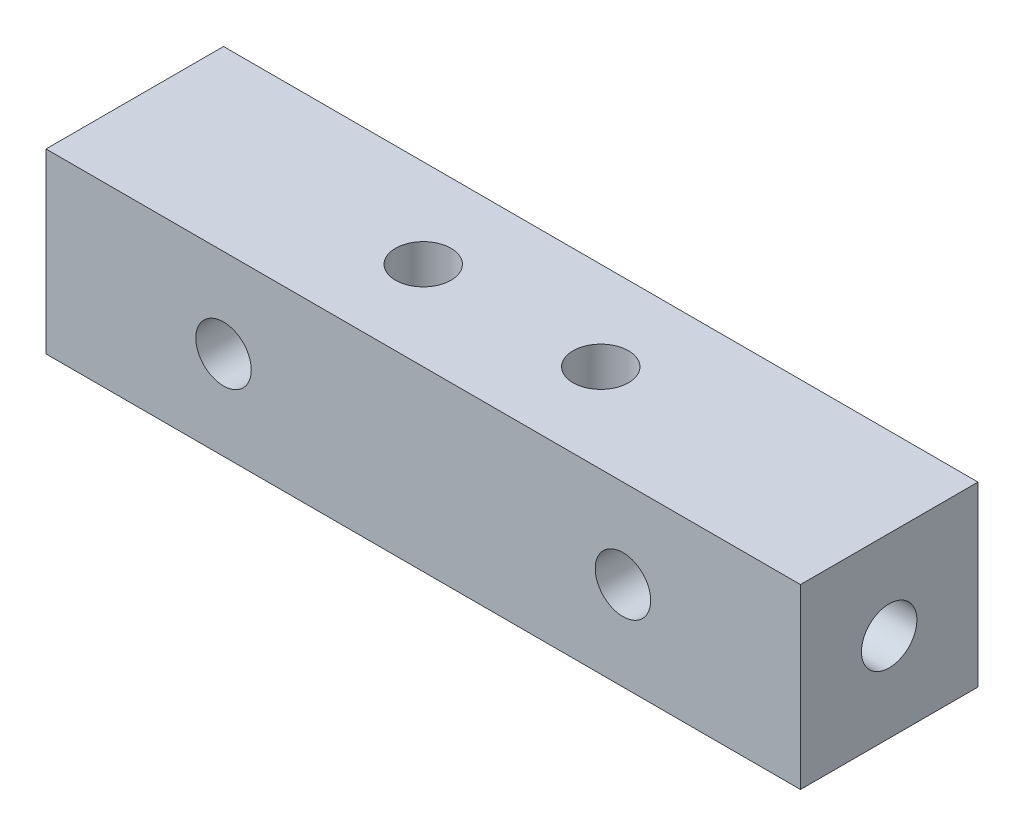
SolidWorks part; units mm, degrees
material "6061 合金"
ref_plane "前视基准面" through (0, 0, 0) normal (0, 0, 1) x (1, 0, 0)
ref_plane "上视基准面" through (0, 0, 0) normal (0, 1, 0) x (1, 0, 0)
ref_plane "右视基准面" through (0, 0, 0) normal (1, 0, 0) x (0, 0, -1)
sketch "草图1" plane through (0, 0, 0) normal (0, 0, 1) x (1, 0, 0)
  line L1 (17, -4) -> (-17, -4)
  line L2 (17, -4) -> (17, 4)
  line L3 (17, 4) -> (-17, 4)
  line L4 (-17, -4) -> (-17, 4)
  line L5 (17, -4) -> (-17, 4) construction
  line L6 (17, 4) -> (-17, -4) construction
  point P0 (0, 0)
  dimension "D1" = 34
  dimension "D2" = 8
extrude "凸台-拉伸1" add sketch "草图1" along normal blind 8
sketch "草图4" plane through (17, 0, 0) normal (1, 0, 0) x (0, 0, -1)
  line L0 (-8, 4) -> (0, -4) construction
  line L1 (0, 4) -> (-8, -4) construction
  point P8 (-4.0037, 0)
sketch "草图7" plane through (17, 0, 0) normal (1, 0, 0) x (0, 0, -1)
  line L0 (-8, 4) -> (0, -4) construction
  line L1 (0, 4) -> (-8, -4) construction
hole_wizard "M3 螺纹孔的螺纹孔钻头2" positions "3D草图6" profile "草图10" hole size "M3" standard "DIN" end condition through all
sketch3d "3D草图6"
  point P0 (17, 0, 4.0037)
sketch "草图10" plane through (17, 0, 4.0037) normal (0, 1, 0) x (0, 0, -1)
  line L0 (0, 0) -> (0, 34)
  line L1 (0, 34) -> (1.25, 34)
  line L2 (1.25, 34) -> (1.25, 0)
  line L5 (1.25, 0) -> (0, 0)
  line L11 (0, -6.35) -> (0, 107.95) construction
  dimension "通孔孔直径" = 2.5
  dimension "通孔孔深度" = 34
sketch "草图11" plane through (0, 0, 8) normal (0, 0, 1) x (1, 0, 0)
  line L0 (-17, 4) -> (-17, -4) construction
  point P0 (-9, 0)
  dimension "D1" = 8
hole_wizard "M3 螺纹孔的螺纹孔钻头3" positions "3D草图7" profile "草图12" hole size "M3" standard "DIN" end condition through all
sketch3d "3D草图7"
  point P0 (-9, 0, 8)
sketch "草图12" plane through (-9, 0, 8) normal (1, 0, 0) x (0, -1, 0)
  line L0 (0, 0) -> (0, 8)
  line L1 (0, 8) -> (1.25, 8)
  line L2 (1.25, 8) -> (1.25, 0)
  line L5 (1.25, 0) -> (0, 0)
  line L11 (0, -6.35) -> (0, 107.95) construction
  dimension "通孔孔直径" = 2.5
  dimension "通孔孔深度" = 8
sketch "草图13" plane through (0, 0, 8) normal (0, 0, 1) x (1, 0, 0)
  line L0 (17, -4) -> (17, 4) construction
  point P0 (9, 0)
  dimension "D1" = 8
hole_wizard "M3 螺纹孔的螺纹孔钻头4" positions "3D草图8" profile "草图14" hole size "M3" standard "DIN" end condition through all
sketch3d "3D草图8"
  point P0 (9, 0, 8)
sketch "草图14" plane through (9, 0, 8) normal (1, 0, 0) x (0, -1, 0)
  line L0 (0, 0) -> (0, 8)
  line L1 (0, 8) -> (1.25, 8)
  line L2 (1.25, 8) -> (1.25, 0)
  line L5 (1.25, 0) -> (0, 0)
  line L11 (0, -6.35) -> (0, 107.95) construction
  dimension "通孔孔直径" = 2.5
  dimension "通孔孔深度" = 8
sketch "草图15" plane through (0, 4, 0) normal (0, 1, 0) x (1, 0, 0)
  line L0 (17, 0) -> (-17, 0) construction
  line L1 (-17, -8) -> (-17, 0) construction
  point P0 (-4, -4)
  dimension "D1" = 4
  dimension "D2" = 13
hole_wizard "M3 螺纹孔的螺纹孔钻头5" positions "3D草图9" profile "草图16" hole size "M3" standard "DIN" end condition through all
sketch3d "3D草图9"
  point P0 (-4, 4, 4)
sketch "草图16" plane through (-4, 4, 4) normal (1, 0, 0) x (0, 0, 1)
  line L0 (0, 0) -> (0, 8)
  line L1 (0, 8) -> (1.25, 8)
  line L2 (1.25, 8) -> (1.25, 0)
  line L5 (1.25, 0) -> (0, 0)
  line L11 (0, -6.35) -> (0, 107.95) construction
  dimension "通孔孔直径" = 2.5
  dimension "通孔孔深度" = 8
sketch "草图17" plane through (0, 4, 0) normal (0, 1, 0) x (1, 0, 0)
  point P0 (4, -4)
  dimension "D1" = 8
hole_wizard "M3 螺纹孔的螺纹孔钻头6" positions "3D草图10" profile "草图18" hole size "M3" standard "DIN" end condition through all
sketch3d "3D草图10"
  point P0 (4, 4, 4)
sketch "草图18" plane through (4, 4, 4) normal (1, 0, 0) x (0, 0, 1)
  line L0 (0, 0) -> (0, 8)
  line L1 (0, 8) -> (1.25, 8)
  line L2 (1.25, 8) -> (1.25, 0)
  line L5 (1.25, 0) -> (0, 0)
  line L11 (0, -6.35) -> (0, 107.95) construction
  dimension "通孔孔直径" = 2.5
  dimension "通孔孔深度" = 8
